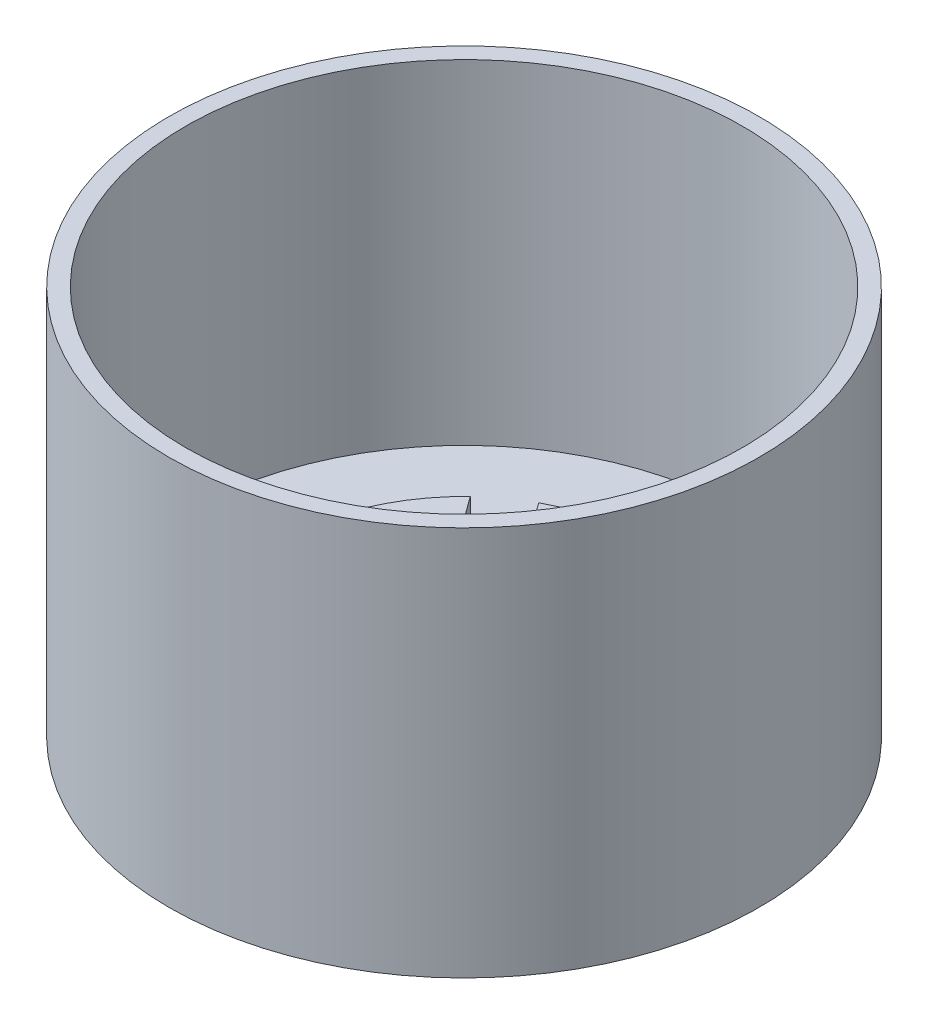
SolidWorks part; units mm, degrees
ref_plane "前视基准面" through (0, 0, 0) normal (0, 0, 1) x (1, 0, 0)
ref_plane "上视基准面" through (0, 0, 0) normal (0, 1, 0) x (1, 0, 0)
ref_plane "右视基准面" through (0, 0, 0) normal (1, 0, 0) x (0, 0, -1)
sketch "草图1" plane through (0, 0, 0) normal (0, 1, 0) x (1, 0, 0)
  circle A0 centre (0, 0) radius 26.5
  dimension "D1" = 53
extrude "凸台-拉伸1" add sketch "草图1" along normal blind 5
sketch "草图2" plane through (0, 5, 0) normal (0, 1, 0) x (1, 0, 0)
  circle A0 centre (0, 0) radius 25
  circle A1 centre (0, 0) radius 26.5
  dimension "D1" = 50
  dimension "D2" = 53
extrude "凸台-拉伸2" add sketch "草图2" along normal blind 30
sketch "草图3" plane through (0, 0, 0) normal (0, -1, 0) x (1, 0, 0)
  circle A0 centre (0, 0) radius 2.1
  dimension "D1" = 4.2
extrude "切除-拉伸1" cut sketch "草图3" against normal blind 10
sketch "草图4" plane through (0, 5, 0) normal (0, 1, 0) x (1, 0, 0)
  line L0 (0, 0) -> (0, -12.7071)
  line L1 (12.4695, -6.3648) -> (9.9066, 9.8924)
  line L2 (9.9066, 9.8924) -> (-6.3469, 12.4786)
  line L3 (-6.3469, 12.4786) -> (-13.8292, -2.1802)
  line L4 (-13.8292, -2.1802) -> (-2.2, -13.8261)
  line L5 (-2.2, -13.8261) -> (12.4695, -6.3648)
  line L6 (13.8292, -2.1802) -> (6.3469, 12.4786)
  line L7 (6.3469, 12.4786) -> (-9.9066, 9.8924)
  line L8 (-9.9066, 9.8924) -> (-12.4695, -6.3648)
  line L9 (-12.4695, -6.3648) -> (2.2, -13.8261)
  line L10 (2.2, -13.8261) -> (13.8292, -2.1802)
  line L11 (-2.2, -13.8261) -> (-2.2, -16.4031)
  line L12 (2.2, -13.8261) -> (2.2, -16.4031)
  line L13 (0, 0) -> (12.0852, -3.9267)
  line L14 (0, 0) -> (7.469, 10.2803)
  line L15 (0, 0) -> (-7.469, 10.2803)
  line L16 (0, 0) -> (-12.0852, -3.9267)
  line L17 (12.4695, -6.3648) -> (14.9205, -7.1612)
  line L18 (13.8292, -2.1802) -> (16.2801, -2.9765)
  line L19 (9.9066, 9.8924) -> (11.4214, 11.9773)
  line L20 (6.3469, 12.4786) -> (7.8617, 14.5635)
  line L21 (-9.9066, 9.8924) -> (-11.4214, 11.9773)
  line L22 (-6.3469, 12.4786) -> (-7.8617, 14.5635)
  line L23 (-13.8292, -2.1802) -> (-16.2801, -2.9765)
  line L24 (-12.4695, -6.3648) -> (-14.9205, -7.1612)
  circle A0 centre (0, 0) radius 14
  circle A1 centre (0, 0) radius 14 construction
  circle A2 centre (0, 0) radius 14 construction
  circle A3 centre (0, 0) radius 16.55
  dimension "D1" = 28
  dimension "D3" = 33.1
  dimension "D2" = 4.4
extrude "凸台-拉伸3" add sketch "草图4" along normal blind 2 contours L21 A3 L23 A0 | L20 A3 L22 A0 | L18 A3 L19 A0 | L12 A3 L17 A0 | L24 A3 L11 A0
